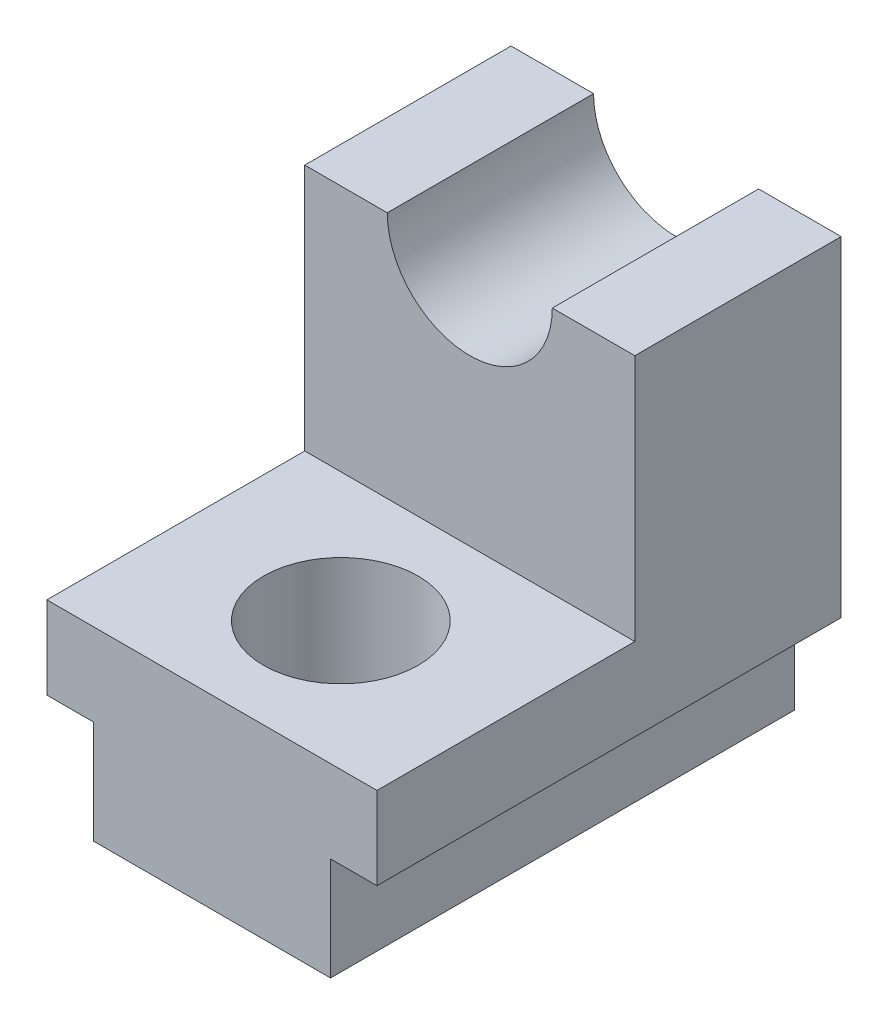
SolidWorks part; units mm, degrees
ref_plane "前视基准面" through (0, 0, 0) normal (0, 0, 1) x (1, 0, 0)
ref_plane "上视基准面" through (0, 0, 0) normal (0, 1, 0) x (1, 0, 0)
ref_plane "右视基准面" through (0, 0, 0) normal (1, 0, 0) x (0, 0, -1)
other "Configuration Table"
sketch "草图1" plane through (0, 0, 0) normal (0, 0, 1) x (1, 0, 0)
  line L0 (0, -166.0717) -> (0, 8137.5119) construction
  line L1 (-11.5, -5) -> (11.5, -5)
  line L2 (-11.5, -5) -> (-11.5, 5)
  line L4 (11.5, -5) -> (11.5, 5)
  line L5 (-11.5, -5) -> (11.5, 5) construction
  line L6 (-11.5, 5) -> (11.5, -5) construction
  line L7 (11.5, 5) -> (16, 5)
  line L8 (16, 5) -> (16, 13)
  line L9 (16, 13) -> (-16, 13)
  line L10 (-16, 5) -> (-16, 13)
  line L11 (-11.5, 5) -> (-16, 5)
  point P0 (0, 0)
  point P9 (16, 10.4202)
  point P13 (0, 13)
  dimension "D1" = 32
  dimension "D2" = 23
  dimension "D3" = 18
  dimension "D4" = 10
extrude "凸台-拉伸1" add sketch "草图1" against normal blind 45
sketch "草图2" plane through (0, 13, 0) normal (0, 1, 0) x (1, 0, 0)
  line L5 (-16, 25) -> (-16, 0) construction
  line L6 (-1016, 12.5) -> (48984, 12.5) construction
  line L7 (-16, 25) -> (16, 25) construction
  line L8 (16, 45) -> (16, 0) construction
  line L9 (16, 45) -> (-16, 45) construction
  circle A0 centre (0, 12.5) radius 7.5
  point P14 (-16, 12.5)
  dimension "D1" = 15
  dimension "D2" = 20
extrude "切除-拉伸2" cut sketch "草图2" against normal blind 24
sketch "草图3" plane through (0, 13, 0) normal (0, 1, 0) x (1, 0, 0)
  line L0 (16, 45) -> (16, 0) construction
  line L1 (-16, 45) -> (16, 45)
  line L2 (-16, 45) -> (-16, 25)
  line L3 (-16, 25) -> (16, 25)
  line L4 (16, 45) -> (16, 25)
  dimension "D1" = 20
extrude "凸台-拉伸4" add sketch "草图3" along normal blind 24
sketch "草图4" plane through (0, 0, -25) normal (0, 0, 1) x (1, 0, 0)
  line L0 (-16, 37) -> (16, 37) construction
  circle A0 centre (0, 37) radius 8
  dimension "D1" = 16
extrude "切除-拉伸3" cut sketch "草图4" against normal blind 24
